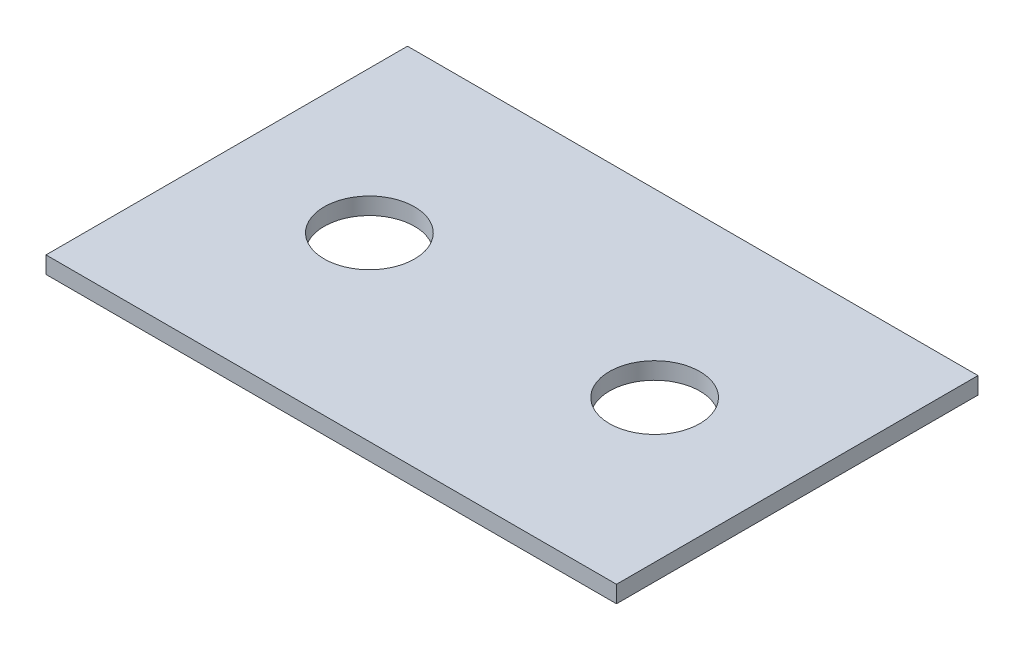
SolidWorks part; units mm, degrees
ref_plane "Front Plane" through (0, 0, 0) normal (0, 0, 1) x (1, 0, 0)
ref_plane "Top Plane" through (0, 0, 0) normal (0, 1, 0) x (1, 0, 0)
ref_plane "Right Plane" through (0, 0, 0) normal (1, 0, 0) x (0, 0, -1)
sketch "Sketch1" plane through (0, 0, 0) normal (0, 1, 0) x (1, 0, 0)
  line L0 (-50.5, 0) -> (0, 0) construction
  line L1 (-50.5, -32) -> (50.5, -32)
  line L2 (-50.5, -32) -> (-50.5, 32)
  line L3 (-50.5, 32) -> (50.5, 32)
  line L4 (50.5, -32) -> (50.5, 32)
  line L5 (-50.5, -32) -> (50.5, 32) construction
  line L6 (-50.5, 32) -> (50.5, -32) construction
  line L7 (0, 0) -> (50.5, 0) construction
  circle A0 centre (-25.25, 0) radius 8
  circle A1 centre (25.25, 0) radius 8
  point P0 (0, 0)
  dimension "D3" = 16
  dimension "D4" = 16
  dimension "D1" = 101
  dimension "D2" = 64
extrude "Boss-Extrude1" add sketch "Sketch1" along normal blind 3
